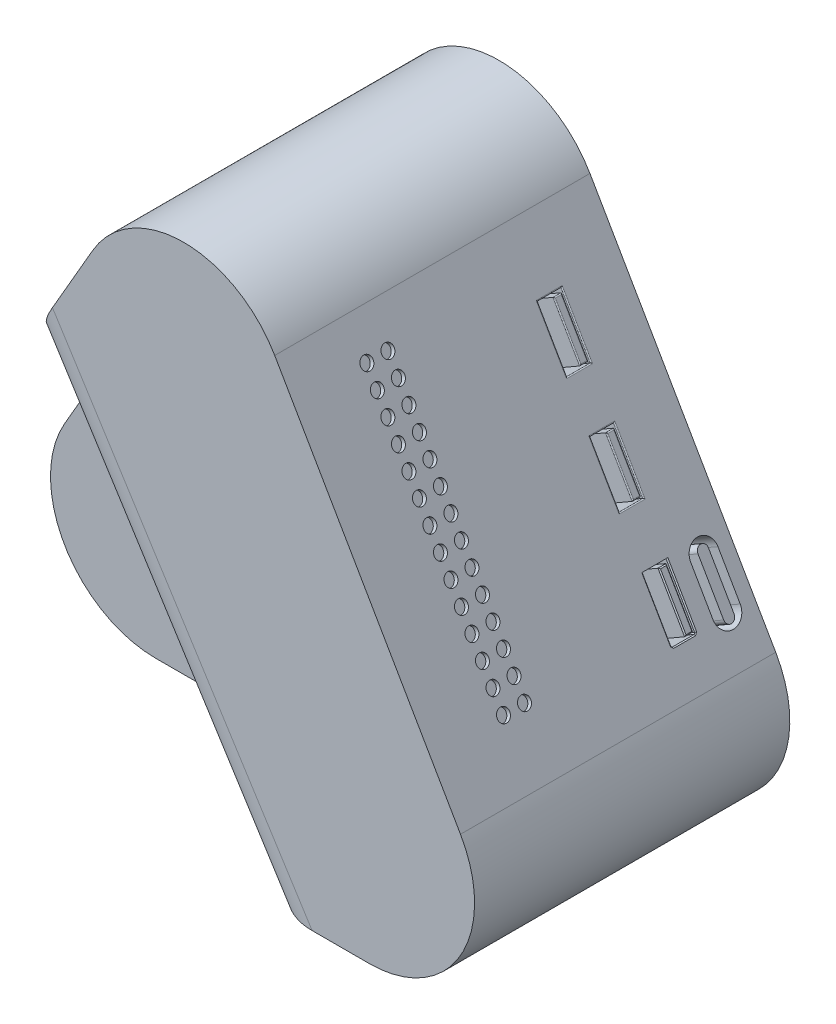
SolidWorks part; units mm, degrees
ref_plane "Front Plane" through (0, 0, 0) normal (0, 0, 1) x (1, 0, 0)
ref_plane "Top Plane" through (0, 0, 0) normal (0, 1, 0) x (1, 0, 0)
ref_plane "Right Plane" through (0, 0, 0) normal (1, 0, 0) x (0, 0, -1)
sketch "Sketch1" plane through (0, 0, 0) normal (0, 0, 1) x (1, 0, 0)
  line L0 (0, 0) -> (0, 56.9423) construction
  line L1 (0, 0) -> (138.3846, 0) construction
  line L2 (-17.6795, 0) -> (17.6795, 0)
  line L3 (26.3397, 15) -> (8.6603, 45.6218)
  line L4 (-26.3397, 15) -> (-8.6603, 45.6218)
  arc A0 (-17.6795, 0) -> (-26.3397, 15) centre (-17.6795, 10) cw
  arc A1 (17.6795, 0) -> (26.3397, 15) centre (17.6795, 10) ccw
  arc A2 (8.6603, 45.6218) -> (-8.6603, 45.6218) centre (0, 40.6218) ccw
  point P6 (0, 0)
  point P7 (0, 0)
  point P11 (-35, 0)
  point P14 (35, 0)
  point P17 (0, 60.6218)
  dimension "D3" = 10
  dimension "D1" = 70
  dimension "D2" = 70
extrude "Boss-Extrude1" add sketch "Sketch1" along normal blind 30
sketch "Sketch2" plane through (26.25, 15.1554, 0) normal (0.866, 0.5, 0) x (0, 0, -1)
  line L0 (-7.9096, 13.7107) -> (-7.9096, 19.2895)
  line L1 (-7.9096, 3.7107) -> (-5.6344, 3.7107)
  line L2 (-7.9096, 3.7107) -> (-7.9096, 9.2895)
  line L3 (-7.9096, 9.2895) -> (-5.6344, 9.2895)
  line L4 (-5.6344, 3.7107) -> (-5.6344, 9.2895)
  line L5 (-7.9096, 13.7107) -> (-5.6344, 13.7107)
  line L6 (-5.6344, 13.7107) -> (-5.6344, 19.2895)
  line L7 (-7.9096, 19.2895) -> (-5.6344, 19.2895)
  line L8 (-7.9096, 23.7107) -> (-7.9096, 29.2895)
  line L9 (-7.9096, 23.7107) -> (-5.6344, 23.7107)
  line L10 (-5.6344, 23.7107) -> (-5.6344, 29.2895)
  line L11 (-7.9096, 29.2895) -> (-5.6344, 29.2895)
  dimension "D1" = 3
extrude "Cut-Extrude1" cut sketch "Sketch2" against normal blind 5
sketch "Sketch3" plane through (21.9199, 12.6554, 0) normal (0.866, 0.5, 0) x (0, 0, -1)
  line L0 (-6.5474, 13.9006) -> (-6.5474, 18.9672)
  line L1 (-6.5474, 3.9006) -> (-5.7853, 3.9006)
  line L2 (-6.5474, 3.9006) -> (-6.5474, 8.9672)
  line L3 (-6.5474, 8.9672) -> (-5.7853, 8.9672)
  line L4 (-5.7853, 3.9006) -> (-5.7853, 8.9672)
  line L5 (-6.5474, 13.9006) -> (-5.7853, 13.9006)
  line L6 (-5.7853, 13.9006) -> (-5.7853, 18.9672)
  line L7 (-6.5474, 18.9672) -> (-5.7853, 18.9672)
  line L8 (-6.5474, 23.9006) -> (-6.5474, 28.9672)
  line L9 (-6.5474, 23.9006) -> (-5.7853, 23.9006)
  line L10 (-5.7853, 23.9006) -> (-5.7853, 28.9672)
  line L11 (-6.5474, 28.9672) -> (-5.7853, 28.9672)
  dimension "D1" = 3
extrude "Boss-Extrude3" add sketch "Sketch3" along normal blind 5
chamfer "Chamfer2" distance 0.1 angle 45 10 edges at (22.9999, 20.7847, 7.9096) (22.9999, 20.7847, 5.6344) (22.2296, 17.119, 7.9096) (20.0645, 15.869, 6.772) (22.2296, 17.119, 5.6344) (24.3946, 18.369, 6.772) (23.0331, 20.7273, 5.7853) (24.2997, 18.5334, 6.1663) (23.0331, 20.7273, 6.5474) (21.7664, 22.9213, 6.1663)
fillet "Fillet1" radius 0.1 4 edges at (18.0331, 29.3876, 5.7853) (16.7664, 31.5815, 6.1663) (18.0331, 29.3876, 6.5474) (19.2997, 27.1937, 6.1663)
fillet "Fillet2" radius 0.1 4 edges at (14.2997, 35.8539, 6.1663) (13.0331, 38.0479, 5.7853) (11.7664, 40.2418, 6.1663) (13.0331, 38.0479, 6.5474)
fillet "Fillet3" radius 0.1 4 edges at (16.6053, 31.8606, 6.772) (17.9999, 29.445, 7.9096) (19.3946, 27.0293, 6.772) (17.9999, 29.445, 5.6344)
fillet "Fillet4" radius 0.1 4 edges at (12.9999, 38.1052, 5.6344) (14.3946, 35.6895, 6.772) (12.9999, 38.1052, 7.9096) (11.6053, 40.5209, 6.772)
sketch "Sketch4" plane through (26.25, 15.1554, 0) normal (0.866, 0.5, 0) x (0, 0, -1)
  line L0 (-2.6011, 3.9701) -> (-2.6011, 8.2049) construction
  line L1 (-3.8958, 3.9701) -> (-3.8958, 8.2049)
  line L2 (-1.3063, 3.9701) -> (-1.3063, 8.2049)
  arc A0 (-3.8958, 3.9701) -> (-1.3063, 3.9701) centre (-2.6011, 3.9701) ccw
  arc A1 (-1.3063, 8.2049) -> (-3.8958, 8.2049) centre (-2.6011, 8.2049) ccw
  point P2 (-2.6011, 6.0875)
extrude "Cut-Extrude2" cut sketch "Sketch4" against normal blind 5
sketch "Sketch5" plane through (21.9199, 12.6554, 0) normal (0.866, 0.5, 0) x (0, 0, -1)
  line L0 (-2.5777, 3.5831) -> (-2.5777, 8.4657) construction
  line L1 (-3.0743, 3.5831) -> (-3.0743, 8.4657)
  line L2 (-2.0812, 3.5831) -> (-2.0812, 8.4657)
  arc A0 (-3.0743, 3.5831) -> (-2.0812, 3.5831) centre (-2.5777, 3.5831) ccw
  arc A1 (-2.0812, 8.4657) -> (-3.0743, 8.4657) centre (-2.5777, 8.4657) ccw
  point P2 (-2.5777, 6.0244)
extrude "Boss-Extrude4" add sketch "Sketch5" along normal blind 5
sketch "Sketch6" plane through (0, 0, 30) normal (0, 0, 1) x (1, 0, 0)
  line L0 (-18.6746, 41.2672) -> (-39.4477, 28.1001)
  line L1 (-39.4477, 28.1001) -> (-49.9404, 21.4492)
  line L2 (-49.9404, 21.4492) -> (-18.6746, -29.5856)
  line L3 (-18.6746, -29.5856) -> (13.3638, -9.2779)
  line L4 (13.3638, -9.2779) -> (-19.0633, 41.8805)
  arc M1 (-26.3397, 15) -> (-17.6795, 0) centre (-17.6795, 10) ccw
  line M2 (-17.6795, 0) -> (17.6795, 0)
  line M6 (-8.6603, 45.6218) -> (-26.3397, 15)
extrude "Cut-Extrude3" cut sketch "Sketch6" against normal blind 15 contours L4 M2 M6 M1
sketch "Sketch7" plane through (5.3382, 3.3836, 0) normal (-0.8446, -0.5354, 0) x (0, 0, 1)
  line L1 (23.9507, 19.8408) -> (19.5107, 19.8408)
  line L2 (23.9507, 19.8408) -> (23.9507, 14.7153)
  line L3 (23.9507, 14.7153) -> (19.5107, 14.7153)
  line L4 (19.5107, 19.8408) -> (19.5107, 14.7153)
extrude "Boss-Extrude5" add sketch "Sketch7" along normal blind 0.4
sketch "Sketch8" plane through (5.0003, 3.1695, 0) normal (-0.8446, -0.5354, 0) x (0, 0, 1)
  circle A0 centre (21.7473, 17.2481) radius 0.5886
extrude "Boss-Extrude6" add sketch "Sketch8" along normal blind 0.4
fillet "Fillet7" radius 4 1 edges at (-3.6333, 17.5374, 15)
sketch "Sketch10" plane through (26.25, 15.1554, 0) normal (0.866, 0.5, 0) x (0, 0, -1)
  circle A0 centre (-23.0625, 5.513) radius 0.5939
  circle A1 centre (-21.0625, 5.513) radius 0.5939
  circle A2 centre (-21.0625, 7.513) radius 0.5939
  circle A3 centre (-21.0625, 9.513) radius 0.5939
  circle A4 centre (-21.0625, 11.513) radius 0.5939
  circle A5 centre (-21.0625, 13.513) radius 0.5939
  circle A6 centre (-21.0625, 15.513) radius 0.5939
  circle A7 centre (-21.0625, 17.513) radius 0.5939
  circle A8 centre (-21.0625, 19.513) radius 0.5939
  circle A9 centre (-21.0625, 21.513) radius 0.5939
  circle A10 centre (-21.0625, 23.513) radius 0.5939
  circle A11 centre (-21.0625, 25.513) radius 0.5939
  circle A12 centre (-21.0625, 27.513) radius 0.5939
  circle A13 centre (-21.0625, 29.513) radius 0.5939
  circle A14 centre (-21.0625, 31.513) radius 0.5939
  circle A15 centre (-23.0625, 7.513) radius 0.5939
  circle A16 centre (-23.0625, 9.513) radius 0.5939
  circle A17 centre (-23.0625, 11.513) radius 0.5939
  circle A18 centre (-23.0625, 13.513) radius 0.5939
  circle A19 centre (-23.0625, 15.513) radius 0.5939
  circle A20 centre (-23.0625, 17.513) radius 0.5939
  circle A21 centre (-23.0625, 19.513) radius 0.5939
  circle A22 centre (-23.0625, 21.513) radius 0.5939
  circle A23 centre (-23.0625, 23.513) radius 0.5939
  circle A24 centre (-23.0625, 25.513) radius 0.5939
  circle A25 centre (-23.0625, 27.513) radius 0.5939
  circle A26 centre (-23.0625, 29.513) radius 0.5939
  circle A27 centre (-23.0625, 31.513) radius 0.5939
  dimension "D1" = 2
  dimension "D2" = 14
extrude "Cut-Extrude4" cut sketch "Sketch10" against normal blind 0.4
fillet "Fillet8" radius 4 1 edges at (-3.6333, 17.5374, 30)
sketch "Sketch11" plane through (0, 0, 15) normal (0, 0, 1) x (1, 0, 0)
  line L0 (-17.007, 31.1648) -> (-18.3665, 28.8101)
  line L1 (-17.007, 31.1648) -> (-26.3397, 15) construction
  line L2 (-18.3665, 28.8101) -> (0, 0)
  line L3 (0, 0) -> (2.747, 0)
  line L4 (-17.6795, 0) -> (2.747, 0) construction
  line L5 (2.747, 0) -> (-17.007, 31.1648) construction
  line L6 (2.747, 0) -> (-17.007, 31.1648)
extrude "Boss-Extrude7" add sketch "Sketch11" along normal blind 3
fillet "Fillet10" radius 1 3 edges at (0, 0, 16.5) (-18.3665, 28.8101, 16.5) (-9.1832, 14.4051, 18)
